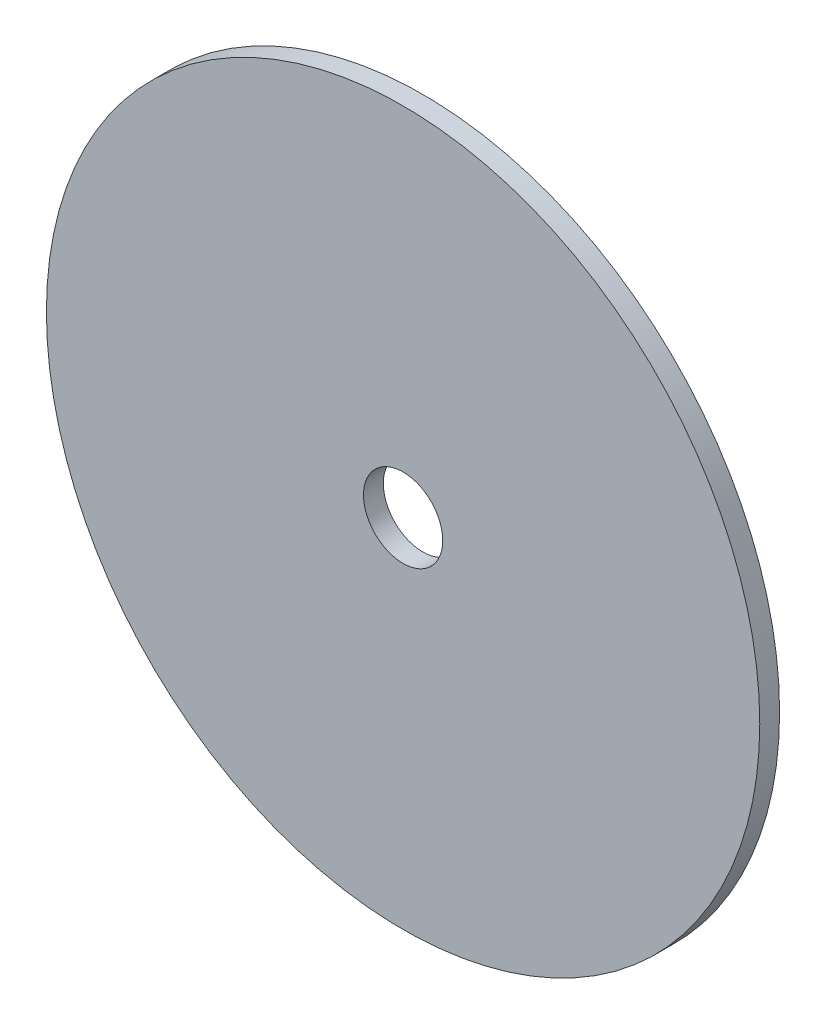
SolidWorks part; units mm, degrees
ref_plane "Front Plane" through (0, 0, 0) normal (0, 0, 1) x (1, 0, 0)
ref_plane "Top Plane" through (0, 0, 0) normal (0, 1, 0) x (1, 0, 0)
ref_plane "Right Plane" through (0, 0, 0) normal (1, 0, 0) x (0, 0, -1)
sketch "Sketch1" plane through (0, 0, 0) normal (0, 0, 1) x (1, 0, 0)
  circle A0 centre (0, 0) radius 114.3
  dimension "D1" = 228.6
extrude "Boss-Extrude1" add sketch "Sketch1" along normal blind 6.35
sketch "Sketch2" plane through (0, 0, 6.35) normal (0, 0, 1) x (1, 0, 0)
  circle A0 centre (0, 0) radius 12.7
  dimension "D1" = 25.4
extrude "Cut-Extrude1" cut sketch "Sketch2" against normal blind 6.35
